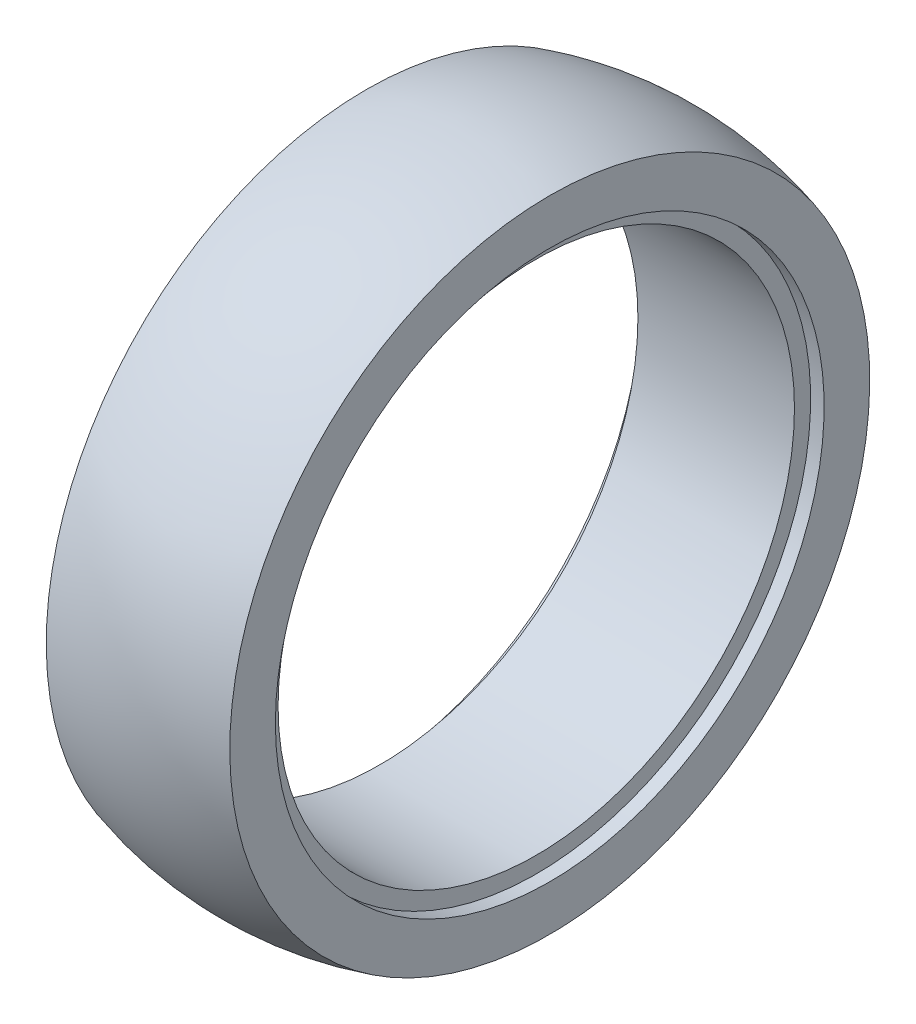
SolidWorks part; units mm, degrees
ref_plane "前视基准面" through (0, 0, 0) normal (0, 0, 1) x (1, 0, 0)
ref_plane "上视基准面" through (0, 0, 0) normal (0, 1, 0) x (1, 0, 0)
ref_plane "右视基准面" through (0, 0, 0) normal (1, 0, 0) x (0, 0, -1)
other "Configuration Table"
sketch "草图1" plane through (0, 0, 0) normal (0, 0, 1) x (1, 0, 0)
  line L0 (0, 0) -> (43.5, 0) construction
  line L3 (0, 71.75) -> (43.5, 71.75)
  line L4 (43.5, 76.25) -> (43.5, 71.75)
  line L5 (0, 71.75) -> (0, 76.25)
  line L6 (47.25, 76.25) -> (43.5, 76.25)
  line L7 (21.75, 0) -> (21.75, 135.0044) construction
  line L8 (47.25, 76.25) -> (47.25, 92.5)
  line L9 (47.25, 92.5) -> (-3.75, 92.5)
  line L10 (47.25, 76.25) -> (43.5, 76.25)
  line L11 (47.25, 86.25) -> (-3.75, 86.25) construction
  line L12 (-3.75, 76.25) -> (0, 76.25)
  line L13 (-3.75, 76.25) -> (-3.75, 92.5)
  arc A0 (47.25, 88.9157) -> (-3.75, 88.9157) centre (21.75, 0) ccw
  point P11 (21.75, 92.5)
  point P16 (45.375, 76.25)
  dimension "D1" = 43.5
  dimension "D2" = 71.75
  dimension "D3" = 76.25
  dimension "D4" = 51
  dimension "D5" = 92.5
  dimension "D6" = 10
revolve "旋转1" add sketch "草图1" angle 360 about L0
